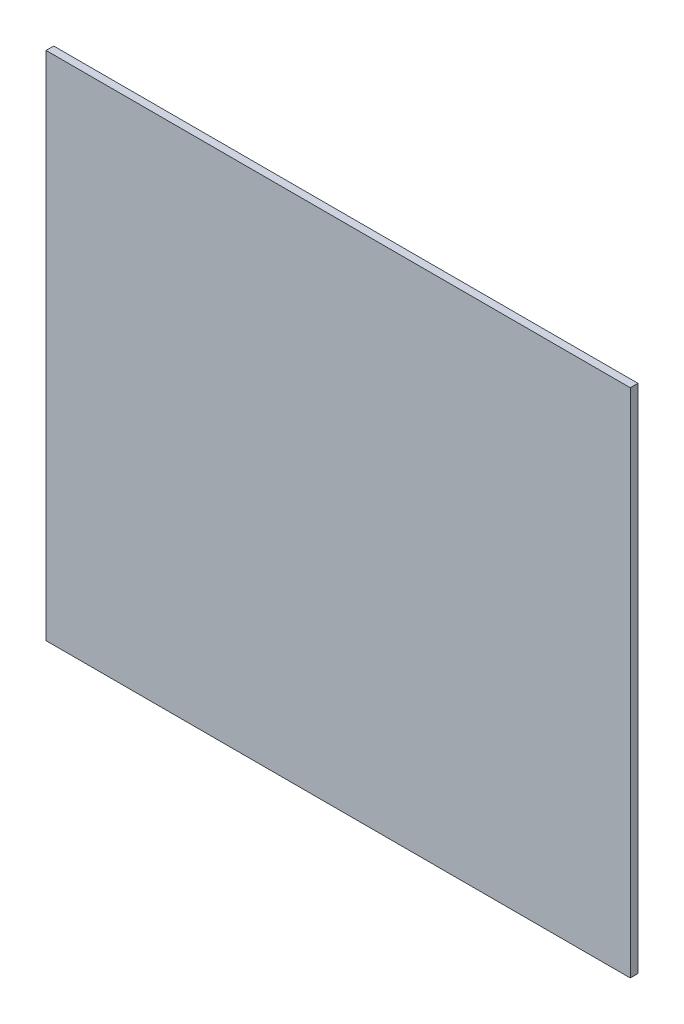
SolidWorks part; units mm, degrees
ref_plane "Front Plane" through (0, 0, 0) normal (0, 0, 1) x (1, 0, 0)
ref_plane "Top Plane" through (0, 0, 0) normal (0, 1, 0) x (1, 0, 0)
ref_plane "Right Plane" through (0, 0, 0) normal (1, 0, 0) x (0, 0, -1)
sketch "Sketch1" plane through (0, 0, 0) normal (0, 0, 1) x (1, 0, 0)
  line L1 (-101.6, -88.9) -> (101.6, -88.9)
  line L2 (-101.6, -88.9) -> (-101.6, 88.9)
  line L3 (-101.6, 88.9) -> (101.6, 88.9)
  line L4 (101.6, -88.9) -> (101.6, 88.9)
  line L5 (-101.6, -88.9) -> (101.6, 88.9) construction
  line L6 (-101.6, 88.9) -> (101.6, -88.9) construction
  point P0 (0, 0)
extrude "Boss-Extrude1" add sketch "Sketch1" along normal blind 2.667
